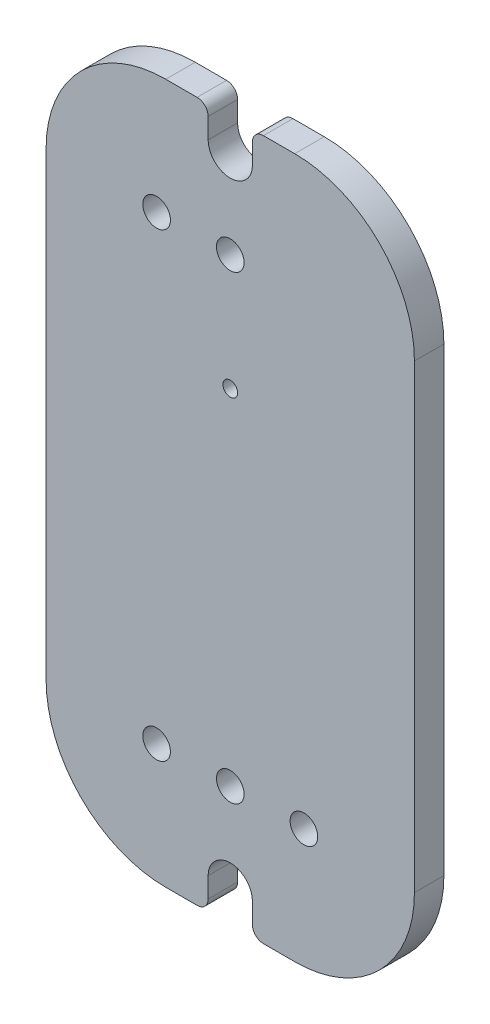
SolidWorks part; units mm, degrees
ref_plane "Front Plane" through (0, 0, 0) normal (0, 0, 1) x (1, 0, 0)
ref_plane "Top Plane" through (0, 0, 0) normal (0, 1, 0) x (1, 0, 0)
ref_plane "Right Plane" through (0, 0, 0) normal (1, 0, 0) x (0, 0, -1)
sketch "Sketch1" plane through (0, 0, 0) normal (0, 0, 1) x (1, 0, 0)
  line L0 (-0.6, 8.65) -> (-0.6, 9.2)
  line L1 (-0.9, 9.5) -> (-1.75, 9.5)
  line L2 (-5, 6.25) -> (-5, -6.25)
  line L3 (-1.75, -9.5) -> (-0.9, -9.5)
  line L4 (-0.6, -9.2) -> (-0.6, -8.65)
  line L5 (0.6, -8.65) -> (0.6, -9.2)
  line L6 (0.9, -9.5) -> (1.75, -9.5)
  line L7 (5, -6.25) -> (5, 6.25)
  line L8 (1.75, 9.5) -> (0.9, 9.5)
  line L9 (0.6, 9.2) -> (0.6, 8.65)
  arc A0 (-0.6, 9.2) -> (-0.9, 9.5) centre (-0.9, 9.2) ccw
  arc A1 (-1.75, 9.5) -> (-5, 6.25) centre (-1.75, 6.25) ccw
  arc A2 (-5, -6.25) -> (-1.75, -9.5) centre (-1.75, -6.25) ccw
  arc A3 (-0.9, -9.5) -> (-0.6, -9.2) centre (-0.9, -9.2) ccw
  arc A4 (-0.6, -8.65) -> (0, -8.05) centre (0, -8.65) cw
  arc A5 (0, -8.05) -> (0.6, -8.65) centre (0, -8.65) cw
  arc A6 (0.6, -9.2) -> (0.9, -9.5) centre (0.9, -9.2) ccw
  arc A7 (1.75, -9.5) -> (5, -6.25) centre (1.75, -6.25) ccw
  arc A8 (5, 6.25) -> (1.75, 9.5) centre (1.75, 6.25) ccw
  arc A9 (0.9, 9.5) -> (0.6, 9.2) centre (0.9, 9.2) ccw
  arc A10 (0.6, 8.65) -> (0, 8.05) centre (0, 8.65) cw
  arc A11 (0, 8.05) -> (-0.6, 8.65) centre (0, 8.65) cw
extrude "BOARD" add sketch "Sketch1" along normal blind 0.8 separate body
sketch "Sketch2" plane through (0, 0, 0) normal (0, 0, 1) x (1, 0, 0)
  circle A0 centre (2, -6.25) radius 0.375
  circle A1 centre (0, -6.25) radius 0.375
  circle A2 centre (-2, -6.25) radius 0.375
  circle A3 centre (-2, 6.25) radius 0.375
  circle A4 centre (0, 6.25) radius 0.375
extrude "NON-PLATED HOLES" cut sketch "Sketch2" along normal through all
sketch "Sketch3" plane through (0, 0, 0) normal (0, 0, 1) x (1, 0, 0)
  circle A0 centre (0, 3.1) radius 0.2
extrude "PLATED HOLES" cut sketch "Sketch3" along normal through all
ref_plane "Plane1" through (0, 0, 150) normal (0, 0, 1) x (1, 0, 0)
